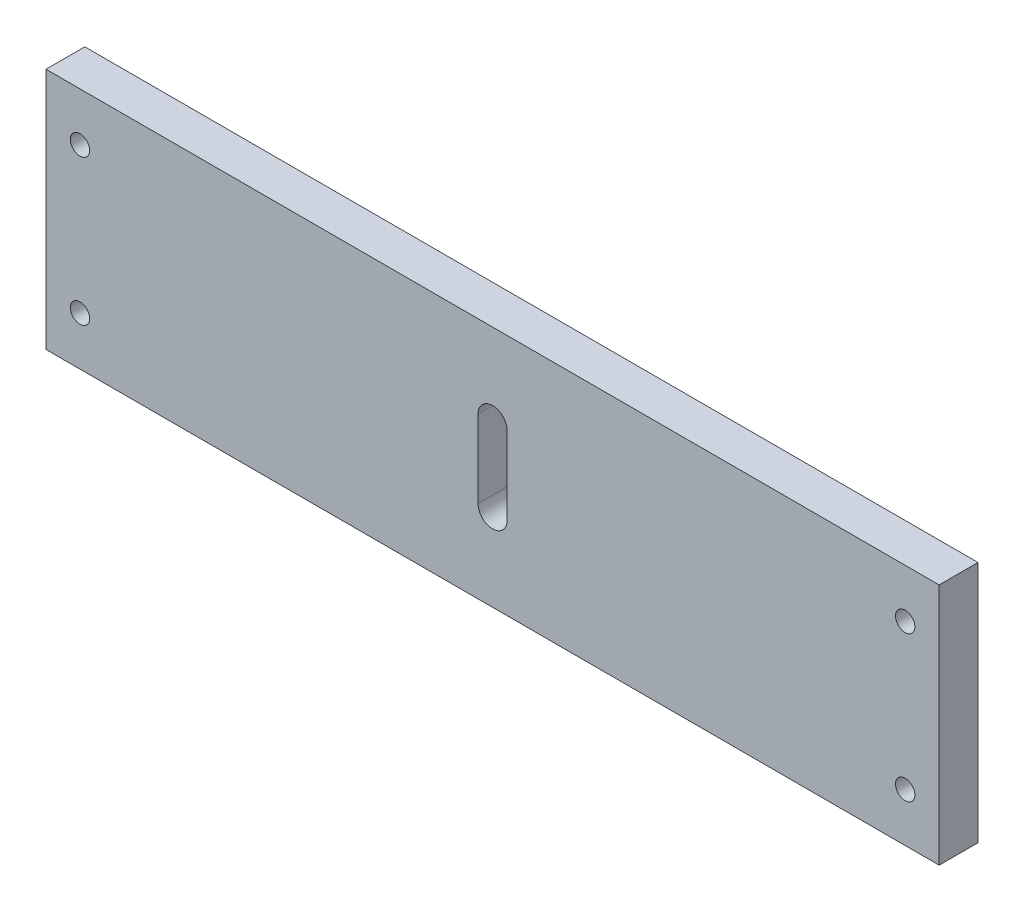
SolidWorks part; units mm, degrees
ref_plane "前视基准面" through (0, 0, 0) normal (0, 0, 1) x (1, 0, 0)
ref_plane "上视基准面" through (0, 0, 0) normal (0, 1, 0) x (1, 0, 0)
ref_plane "右视基准面" through (0, 0, 0) normal (1, 0, 0) x (0, 0, -1)
sketch "草图1" plane through (0, 0, 0) normal (0, 0, 1) x (1, 0, 0)
  line L0 (3131.8374, 1605.5943) -> (3131.8374, 1630.5943)
  line L1 (3131.8374, 1630.5943) -> (3223.8374, 1630.5943)
  line L2 (3223.8374, 1630.5943) -> (3223.8374, 1605.5943)
  line L3 (3131.8374, 1605.5943) -> (3223.8374, 1605.5943)
  line L4 (3179.3374, 1622.0943) -> (3179.3374, 1614.0943)
  line L5 (3176.3374, 1614.0943) -> (3176.3374, 1622.0943)
  circle A0 centre (3135.3374, 1625.5943) radius 1
  circle A1 centre (3135.3374, 1610.5943) radius 1
  circle A2 centre (3220.3374, 1610.5943) radius 1
  circle A3 centre (3220.3374, 1625.5943) radius 1
  arc A4 (3179.3374, 1622.0943) -> (3176.3374, 1622.0943) centre (3177.8374, 1622.0943) ccw
  arc A5 (3176.3374, 1614.0943) -> (3179.3374, 1614.0943) centre (3177.8374, 1614.0943) ccw
extrude "凸台-拉伸1" add sketch "草图1" along normal blind 4
